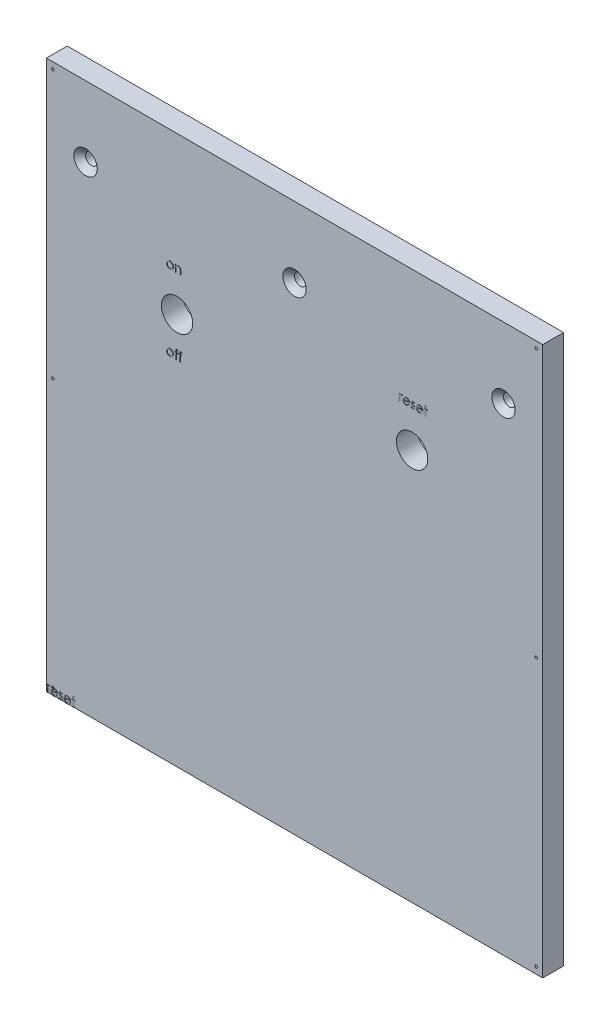
SolidWorks part; units mm, degrees
material "Cedro"
ref_plane "Plano frontal" through (0, 0, 0) normal (0, 0, 1) x (1, 0, 0)
ref_plane "Plano superior" through (0, 0, 0) normal (0, 1, 0) x (1, 0, 0)
ref_plane "Plano direito" through (0, 0, 0) normal (1, 0, 0) x (0, 0, -1)
sketch "Esboço1" plane through (0, 0, 0) normal (0, 0, 1) x (1, 0, 0)
  line L1 (0, 0) -> (190, 0)
  line L2 (0, 0) -> (0, 210)
  line L3 (0, 210) -> (190, 210)
  line L4 (190, 0) -> (190, 210)
  dimension "D1" = 210
  dimension "D2" = 190
extrude "Ressalto-extrusão1" add sketch "Esboço1" along normal blind 8
sketch "Esboço2" plane through (0, 0, 8) normal (0, 0, 1) x (1, 0, 0)
  line L0 (190, 210) -> (0, 210) construction
  line L1 (0, 210) -> (0, 0) construction
  line L2 (190, 0) -> (190, 210) construction
  circle A0 centre (50, 150) radius 6
  circle A1 centre (140, 150) radius 6
  dimension "D1" = 12
  dimension "D2" = 60
  dimension "D3" = 50
  dimension "D4" = 50
  dimension "D5" = 60
extrude "Corte-extrusão1" cut sketch "Esboço2" against normal through all
sketch "Esboço3" plane through (0, 0, 8) normal (0, 0, 1) x (1, 0, 0)
  line L0 (0, 210) -> (0, 0) construction
  line L1 (190, 0) -> (190, 210) construction
  line L2 (0, 0) -> (190, 0) construction
  line L3 (190, 210) -> (0, 210) construction
  point P0 (2.5, 2.5)
  point P1 (187.5, 2.5)
  point P2 (187.5, 207.5)
  point P3 (2.5, 207.5)
  point P12 (2.5, 105)
  point P13 (187.5, 105)
  point P14 (0, 105)
  point P15 (190, 105)
  dimension "D1" = 2.5
  dimension "D2" = 2.5
  dimension "D3" = 2.5
  dimension "D4" = 2.5
  dimension "D5" = 2.5
  dimension "D6" = 2.5
  dimension "D7" = 2.5
  dimension "D8" = 2.5
  dimension "D9" = 2.5
  dimension "D10" = 2.5
hole_wizard "Furo de diâmetro Ø1.0 (1)1" positions "3DSketch1" profile "Esboço4" hole size "Ø1.0" standard "Ansi Metric" end condition through all
sketch3d "3DSketch1"
  point P0 (2.5, 207.5, 8)
  point P3 (2.5, 105, 8)
  point P6 (187.5, 207.5, 8)
  point P9 (187.5, 105, 8)
  point P12 (2.5, 2.5, 8)
  point P15 (187.5, 2.5, 8)
sketch "Esboço4" plane through (2.5, 207.5, 8) normal (1, 0, 0) x (0, -1, 0)
  line L0 (0, 0) -> (0, 8)
  line L1 (0, 8) -> (0.5, 8)
  line L2 (0.5, 8) -> (0.5, 0)
  line L5 (0.5, 0) -> (0, 0)
  line L11 (0, -6.35) -> (0, 107.95) construction
  dimension "Thru Hole Dia." = 1
  dimension "Thru Hole Depth" = 8
sketch "Esboço5" plane through (0, 0, 8) normal (0, 0, 1) x (1, 0, 0)
  line L0 (0, 183) -> (190, 183) construction
  line L1 (0, 210) -> (0, 0) construction
  line L2 (190, 0) -> (190, 210) construction
  point P7 (15, 183)
  point P8 (95, 183)
  point P9 (175, 183)
  dimension "D1" = 27
  dimension "D2" = 15
  dimension "D3" = 15
hole_wizard "Escareado para SFHCS M41" positions "3DSketch2" profile "Esboço6" countersink size "M4" standard "Ansi Metric" end condition through all
sketch3d "3DSketch2"
  point P0 (15, 183, 8)
  point P3 (95, 183, 8)
  point P6 (175, 183, 8)
sketch "Esboço6" plane through (15, 183, 8) normal (1, 0, 0) x (0, -1, 0)
  line L0 (0, 0) -> (0, 8)
  line L1 (0, 8) -> (2.25, 8)
  line L2 (2.25, 8) -> (2.25, 2.23)
  line L3 (2.25, 2.23) -> (4.48, 0)
  line L5 (4.48, 0) -> (0, 0)
  line L6 (-2.25, 2.23) -> (-4.48, 0) construction
  line L11 (0, -6.35) -> (0, 107.95) construction
  dimension "Thru Hole Dia." = 4.5
  dimension "Thru Hole Depth" = 8
  dimension "Near C'Sink Dia." = 8.96
  dimension "Near C'Sink Angle" = 90
sketch "Esboço7" plane through (0, 0, 8) normal (0, 0, 1) x (1, 0, 0)
  text T0 "on\r\n"
  text T1 "off"
  text T2 "reset\r\n"
  text T3 "reset"
extrude "Ressalto-extrusão3" add sketch "Esboço7" along normal blind 0.1
